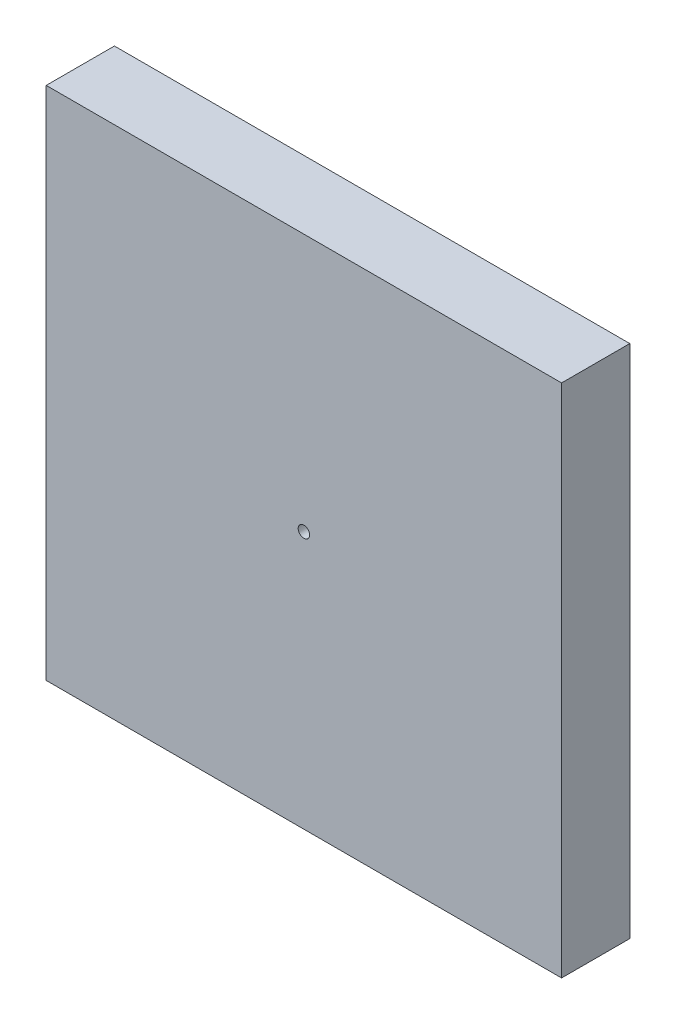
SolidWorks part; units mm, degrees
material "Acrylic (Medium-high impact)"
ref_plane "Front Plane" through (0, 0, 0) normal (0, 0, 1) x (1, 0, 0)
ref_plane "Top Plane" through (0, 0, 0) normal (0, 1, 0) x (1, 0, 0)
ref_plane "Right Plane" through (0, 0, 0) normal (1, 0, 0) x (0, 0, -1)
sketch "Sketch1" plane through (0, 0, 0) normal (0, 0, 1) x (1, 0, 0)
  line L0 (45, -40) -> (135, -40)
  line L1 (135, -40) -> (135, 50)
  line L2 (135, 50) -> (45, 50)
  line L3 (45, 50) -> (45, -40)
  circle A0 centre (90, 5) radius 1
  dimension "D3" = 2
  dimension "D1" = 90
  dimension "D2" = 90
extrude "Boss-Extrude1" add sketch "Sketch1" along normal blind 11.91
